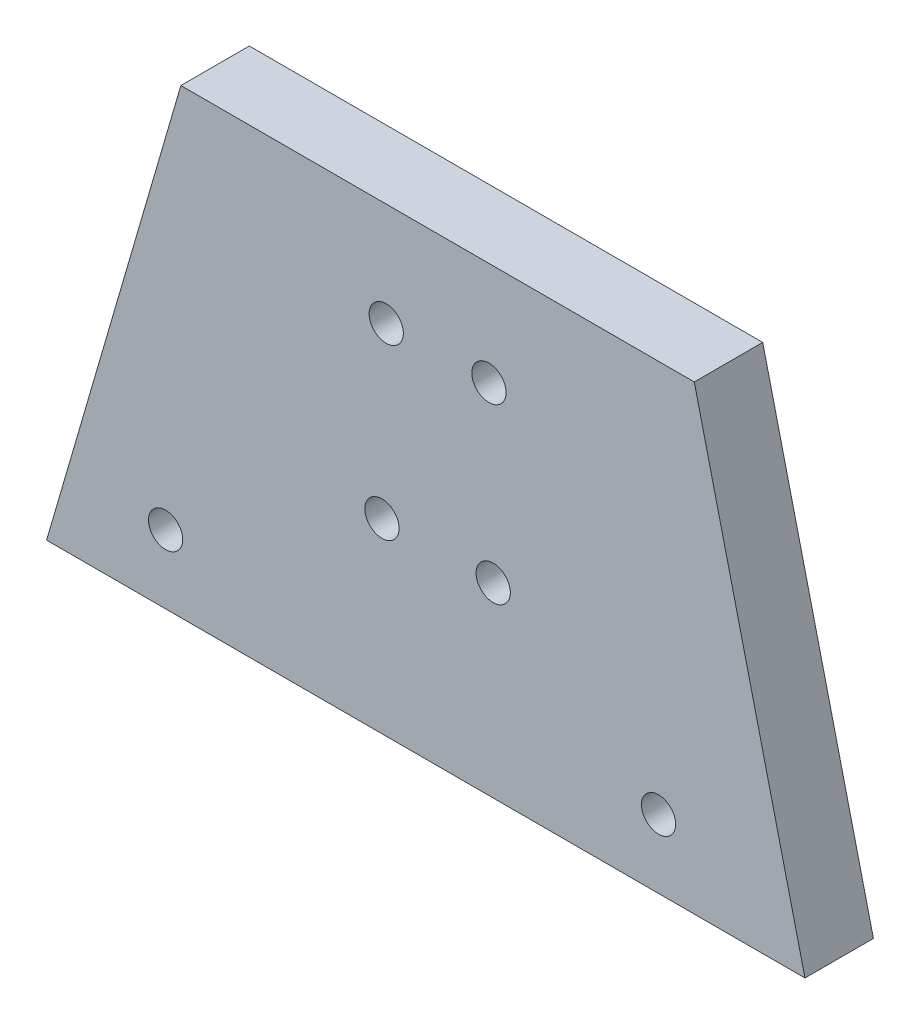
SolidWorks part; units mm, degrees
ref_plane "前视基准面" through (0, 0, 0) normal (0, 0, 1) x (1, 0, 0)
ref_plane "上视基准面" through (0, 0, 0) normal (0, 1, 0) x (1, 0, 0)
ref_plane "右视基准面" through (0, 0, 0) normal (1, 0, 0) x (0, 0, -1)
sketch "草图1" plane through (0, 0, 0) normal (0, 0, 1) x (1, 0, 0)
  line L0 (17.3193, 114.6513) -> (167.3193, 114.6513)
  line L1 (167.3193, 114.6513) -> (199.6583, -20.0026)
  line L2 (199.6583, -20.0026) -> (-21.9151, -20.0026)
  line L3 (-21.9151, -20.0026) -> (17.3193, 114.6513)
  point P2 (199.603, -19.7721)
  point P5 (0, 0)
  point P6 (-21.9151, -20.0026)
  dimension "D1" = 150
  dimension "D4" = 150
extrude "凸台-拉伸1" add sketch "草图1" along normal blind 20
sketch "草图2" plane through (0, 0, 20) normal (0, 0, 1) x (1, 0, 0)
  circle A0 centre (77.3193, 84.433) radius 5
  circle A1 centre (76.0693, 34.4486) radius 5
  circle A2 centre (108.5693, 34.4486) radius 5
  circle A3 centre (107.3193, 84.433) radius 5
  dimension "D1" = 50
  dimension "D3" = 32.5
  dimension "D4" = 30
  dimension "D2" = 50
extrude "切除-拉伸1" cut sketch "草图2" against normal through all
sketch "草图3" plane through (0, 0, 20) normal (0, 0, 1) x (1, 0, 0)
  line L5 (60.0829, -11.8014) -> (92.6872, -11.8014)
  line L6 (60.0829, -11.8014) -> (60.0829, -14.7173)
  line L7 (60.0829, -14.7173) -> (92.6872, -14.7173)
  line L8 (92.6872, -11.8014) -> (92.6872, -14.7173)
  line L12 (62.5136, 83.4201) -> (62.5136, 80.8595)
  line L13 (71.8301, 83.4201) -> (71.8301, 80.8595)
  line L14 (71.8301, 80.8595) -> (62.5136, 80.8595)
  line L15 (62.5136, 83.4201) -> (71.8301, 83.4201)
  line L16 (82.8362, 83.4201) -> (82.8362, 80.8595)
  line L17 (82.8362, 80.8595) -> (94.52, 80.8595)
  line L18 (82.8362, 83.4201) -> (94.52, 83.4201)
  line L19 (94.52, 83.4201) -> (94.52, 80.8595)
extrude "凸台-拉伸2" add sketch "草图3" against normal blind 48
sketch "草图5" plane through (0, 0, 0) normal (0, 0, -1) x (-1, 0, 0)
  line L3 (21.9151, -20.0026) -> (-199.6583, -20.0026) construction
  circle A0 centre (-156.8864, -0.0026) radius 5
  circle A2 centre (-12.8536, -0.0026) radius 5
  point P4 (-156.8864, 0)
  point P5 (-12.8536, 0)
  dimension "D3" = 20
  dimension "D4" = 20
extrude "切除-拉伸2" cut sketch "草图5" against normal blind 28
